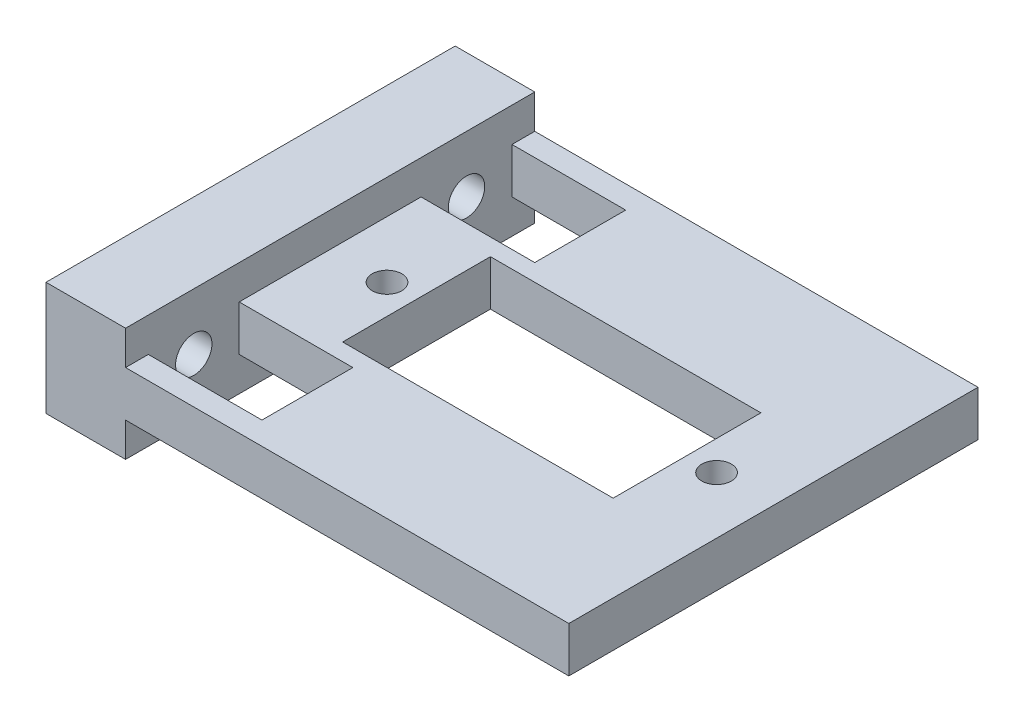
SolidWorks part; units mm, degrees
ref_plane "Front Plane" through (0, 0, 0) normal (0, 0, 1) x (1, 0, 0)
ref_plane "Top Plane" through (0, 0, 0) normal (0, 1, 0) x (1, 0, 0)
ref_plane "Right Plane" through (0, 0, 0) normal (1, 0, 0) x (0, 0, -1)
sketch "Servo_shelf_profile" plane through (0, 0, 0) normal (0, 1, 0) x (1, 0, 0)
  line L1 (-21, -18) -> (25, -18)
  line L2 (-21, -18) -> (-21, 18)
  line L3 (-21, 18) -> (25, 18)
  line L4 (25, -18) -> (25, 18)
  dimension "D1" = 46
  dimension "D2" = 36
  dimension "D3" = 25
  dimension "D4" = 18
extrude "Servo_shelf" add sketch "Servo_shelf_profile" along normal blind 4 from offset 26
sketch "Rear_clamping_block_profile" plane through (0, 0, 0) normal (0, 0, 1) x (1, 0, 0)
  line L1 (-21, 23) -> (-14, 23)
  line L2 (-21, 23) -> (-21, 33)
  line L3 (-21, 33) -> (-14, 33)
  line L4 (-14, 23) -> (-14, 33)
  dimension "D1" = 7
  dimension "D2" = 10
  dimension "D3" = 14
  dimension "D4" = 23
extrude "Rear_clamping_block" add sketch "Rear_clamping_block_profile" along normal blind 36 from offset 18
sketch "Servo_body_window_profile" plane through (0, 0, 0) normal (0, 1, 0) x (1, 0, 0)
  line L1 (-6.4, -6.5) -> (17.4, -6.5)
  line L2 (-6.4, -6.5) -> (-6.4, 6.5)
  line L3 (-6.4, 6.5) -> (17.4, 6.5)
  line L4 (17.4, -6.5) -> (17.4, 6.5)
  dimension "D1" = 23.8
  dimension "D2" = 13
  dimension "D3" = 17.4
  dimension "D4" = 6.5
extrude "Servo_body_window" cut sketch "Servo_body_window_profile" along normal through all from offset 25
sketch "Yaw_servo_M2_fasteners_profile" plane through (0, 0, 0) normal (0, 1, 0) x (1, 0, 0)
  circle A0 centre (-9, 0) radius 1.3
  circle A1 centre (20, 0) radius 1.3
  dimension "D1" = 2.6
  dimension "D2" = 2.6
  dimension "D3" = 20
  dimension "D4" = 9
extrude "Yaw_servo_M2_fasteners" cut sketch "Yaw_servo_M2_fasteners_profile" along normal through all from offset 25
sketch "Left_nut_access_profile" plane through (0, 0, 0) normal (0, 1, 0) x (1, 0, 0)
  line L1 (-14, 8) -> (-4, 8)
  line L2 (-14, 8) -> (-14, 16)
  line L3 (-14, 16) -> (-4, 16)
  line L4 (-4, 8) -> (-4, 16)
  dimension "D1" = 10
  dimension "D2" = 8
  dimension "D3" = 4
  dimension "D4" = 8
extrude "Left_nut_access" cut sketch "Left_nut_access_profile" along normal through all from offset 20
sketch "Right_nut_access_profile" plane through (0, 0, 0) normal (0, 1, 0) x (1, 0, 0)
  line L1 (-14, -16) -> (-4, -16)
  line L2 (-14, -16) -> (-14, -8)
  line L3 (-14, -8) -> (-4, -8)
  line L4 (-4, -16) -> (-4, -8)
  dimension "D1" = 10
  dimension "D2" = 8
  dimension "D3" = 4
  dimension "D4" = 8
extrude "Right_nut_access" cut sketch "Right_nut_access_profile" along normal through all from offset 20
sketch "Rear_clamping_M3_profile" plane through (0, 0, 0) normal (1, 0, 0) x (0, 0, -1)
  circle A0 centre (12, 28) radius 1.6
  circle A1 centre (-12, 28) radius 1.6
  dimension "D1" = 3.2
  dimension "D2" = 3.2
  dimension "D3" = 12
  dimension "D4" = 12
  dimension "D5" = 28
extrude "Rear_clamping_M3_holes" cut sketch "Rear_clamping_M3_profile" along normal blind 11 from offset 25
